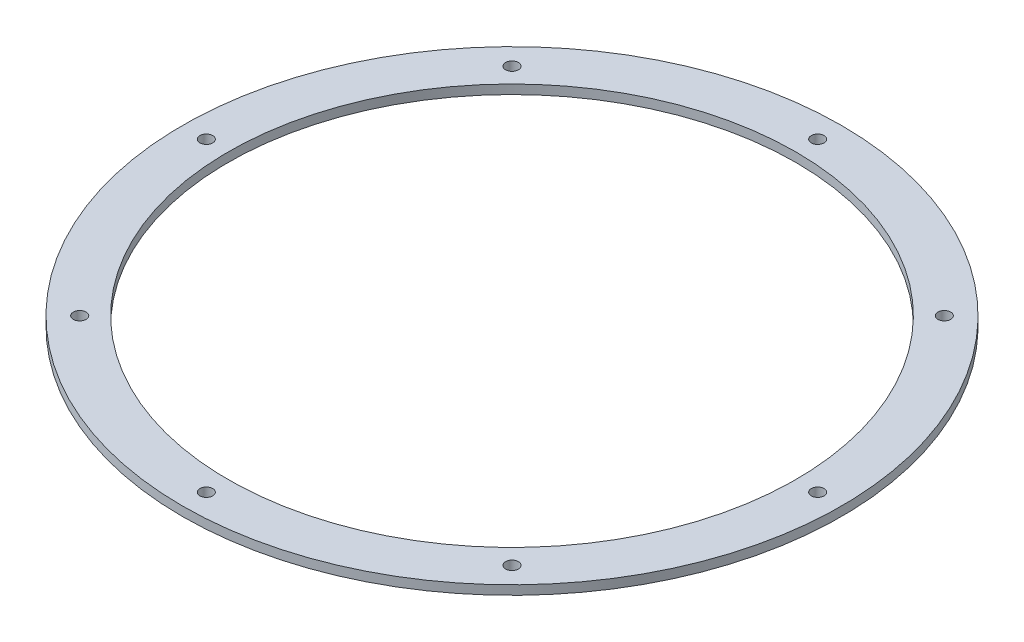
SolidWorks part; units mm, degrees
material "Thornel Mat VMA"
ref_plane "前视基准面" through (0, 0, 0) normal (0, 0, 1) x (1, 0, 0)
ref_plane "上视基准面" through (0, 0, 0) normal (0, 1, 0) x (1, 0, 0)
ref_plane "右视基准面" through (0, 0, 0) normal (1, 0, 0) x (0, 0, -1)
other "Configuration Table"
sketch "草图1" plane through (0, 0, 0) normal (0, 0, 1) x (1, 0, 0)
  line L0 (0, 0) -> (0, 6.6956) construction
  line L2 (93.08, 0) -> (108.08, 0)
  line L3 (93.08, 0) -> (93.08, 3)
  line L4 (93.08, 3) -> (108.08, 3)
  line L5 (108.08, 0) -> (108.08, 3)
  dimension "D1" = 3
  dimension "D2" = 15
  dimension "D3" = 93.08
revolve "旋转1" add sketch "草图1" angle 360 about L0
sketch "草图3" plane through (0, 3, 0) normal (0, 1, 0) x (1, 0, 0)
  circle A0 centre (0, 0) radius 100.25 construction
  circle A2 centre (-100.25, 0) radius 2.1
  circle A3 centre (-70.8875, 70.8875) radius 2.1
  circle A4 centre (0, 100.25) radius 2.1
  circle A5 centre (70.8875, 70.8875) radius 2.1
  circle A6 centre (100.25, 0) radius 2.1
  circle A7 centre (70.8875, -70.8875) radius 2.1
  circle A8 centre (0, -100.25) radius 2.1
  circle A9 centre (-70.8875, -70.8875) radius 2.1
  dimension "D1" = 200.5
  dimension "D2" = 4.2
  dimension "D3" = 8
extrude "切除-拉伸2" cut sketch "草图3" against normal blind 10
